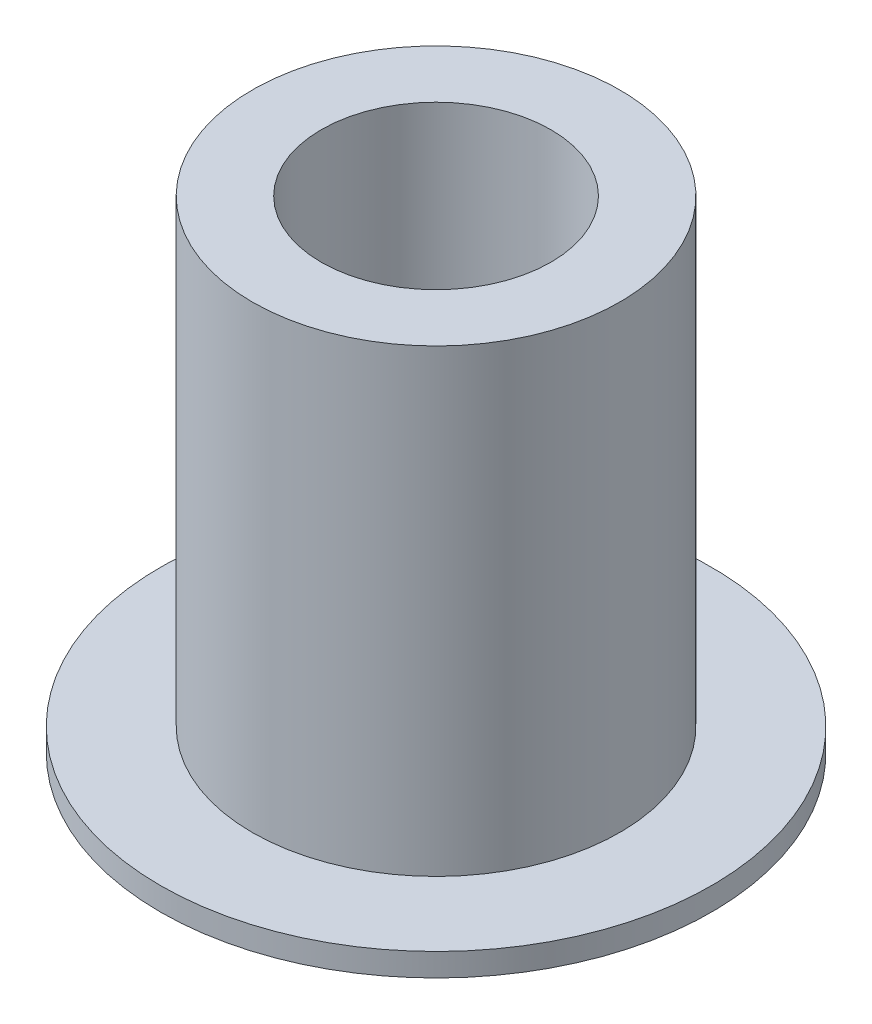
SolidWorks part; units mm, degrees
material "Aleación 1060"
ref_plane "Alzado" through (0, 0, 0) normal (0, 0, 1) x (1, 0, 0)
ref_plane "Planta" through (0, 0, 0) normal (0, 1, 0) x (1, 0, 0)
ref_plane "Vista lateral" through (0, 0, 0) normal (1, 0, 0) x (0, 0, -1)
sketch "Croquis2" plane through (0, 0, 0) normal (0, 1, 0) x (1, 0, 0)
  circle A0 centre (0, 0) radius 6
  dimension "D1" = 12
extrude "Saliente-Extruir1" add sketch "Croquis2" along normal blind 0.5
sketch "Croquis3" plane through (0, 0.5, 0) normal (0, 1, 0) x (1, 0, 0)
  circle A0 centre (0, 0) radius 4
  circle A1 centre (0, 0) radius 2.5
  dimension "D1" = 8
  dimension "D2" = 5
extrude "Saliente-Extruir2" add sketch "Croquis3" along normal blind 10 contours A0 | A1
